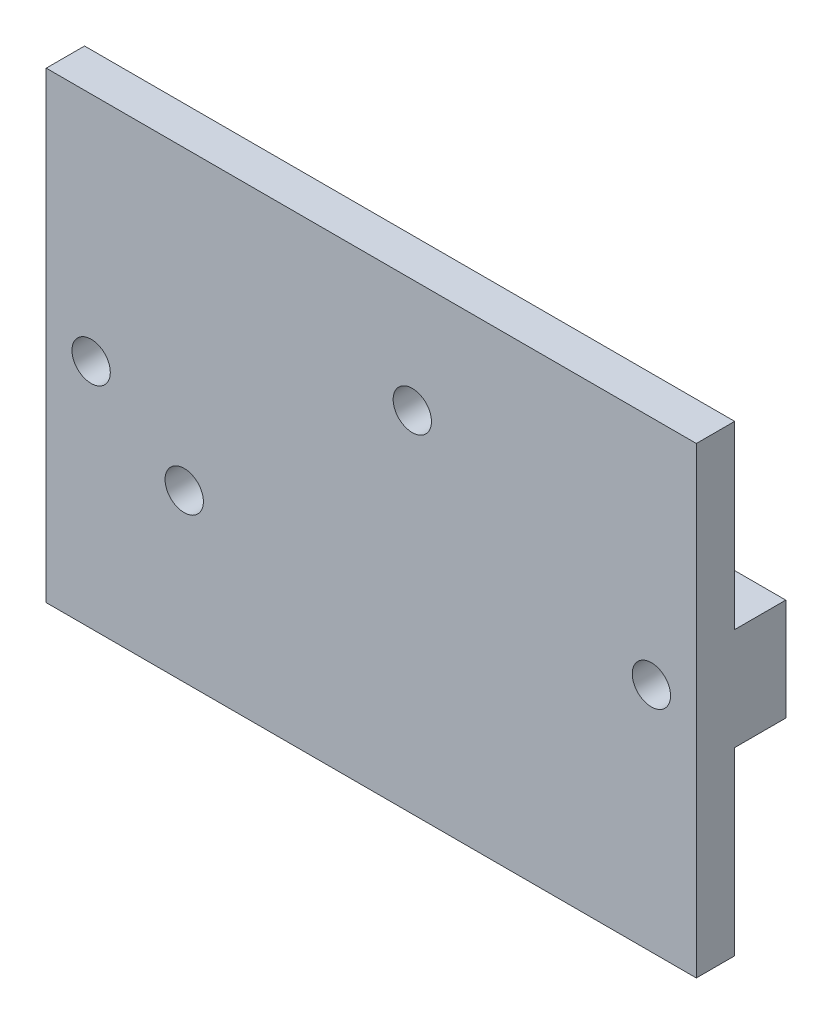
SolidWorks part; units mm, degrees
ref_plane "前视基准面" through (0, 0, 0) normal (0, 0, 1) x (1, 0, 0)
ref_plane "上视基准面" through (0, 0, 0) normal (0, 1, 0) x (1, 0, 0)
ref_plane "右视基准面" through (0, 0, 0) normal (1, 0, 0) x (0, 0, -1)
other "Configuration Table"
sketch "草图1" plane through (0, 0, 0) normal (0, 0, 1) x (1, 0, 0)
  line L0 (43.85, 0) -> (0, 0) construction
  line L1 (-3.515, -5.115) -> (7.285, -5.115) construction
  line L2 (-3.515, 18.115) -> (47.365, 18.115)
  line L3 (-3.515, 18.115) -> (-3.515, -18.115)
  line L4 (-3.515, -18.115) -> (47.365, -18.115)
  line L5 (47.365, 18.115) -> (47.365, -18.115)
  line L6 (-3.515, 18.115) -> (47.365, -18.115) construction
  line L7 (-3.515, -18.115) -> (47.365, 18.115) construction
  circle A0 centre (0, 0) radius 1.5
  circle A1 centre (43.85, 0) radius 1.5
  circle A2 centre (7.285, -5.115) radius 1.5
  circle A3 centre (25.135, 9.235) radius 1.5
  point P5 (21.925, 0)
  dimension "D1" = 43.85
  dimension "D2" = 3
  dimension "D3" = 3
  dimension "D8" = 3
  dimension "D9" = 17.85
  dimension "D11" = 3
  dimension "D4" = 50.88
  dimension "D5" = 36.23
  dimension "D6" = 10.8
  dimension "D7" = 13
  dimension "D10" = 14.35
extrude "凸台-拉伸1" add sketch "草图1" along normal blind 3
sketch "草图2" plane through (0, 0, 0) normal (0, 0, -1) x (-1, 0, 0)
  line L0 (3.515, 18.115) -> (3.515, -18.115) construction
  line L1 (3.515, -4) -> (-2.8465, -4)
  line L2 (3.515, -4) -> (3.515, 4)
  line L3 (3.515, 4) -> (-2.8465, 4)
  line L4 (-2.8465, -4) -> (-2.8465, 4)
  line L5 (-47.365, -18.115) -> (-47.365, 18.115) construction
  line L6 (-47.365, -4) -> (-40.4073, -4)
  line L7 (-47.365, -4) -> (-47.365, 4)
  line L8 (-47.365, 4) -> (-40.4073, 4)
  line L9 (-40.4073, -4) -> (-40.4073, 4)
  circle A1 centre (-43.85, 0) radius 1.5 construction
  circle A2 centre (0, 0) radius 1.5 construction
  circle A3 centre (-43.85, 0) radius 2.5
  circle A4 centre (0, 0) radius 2.5
  dimension "D3" = 4
  dimension "D4" = 4
  dimension "D5" = 5
  dimension "D6" = 5
  dimension "D1" = 8
  dimension "D2" = 8
extrude "凸台-拉伸2" add sketch "草图2" along normal blind 4
